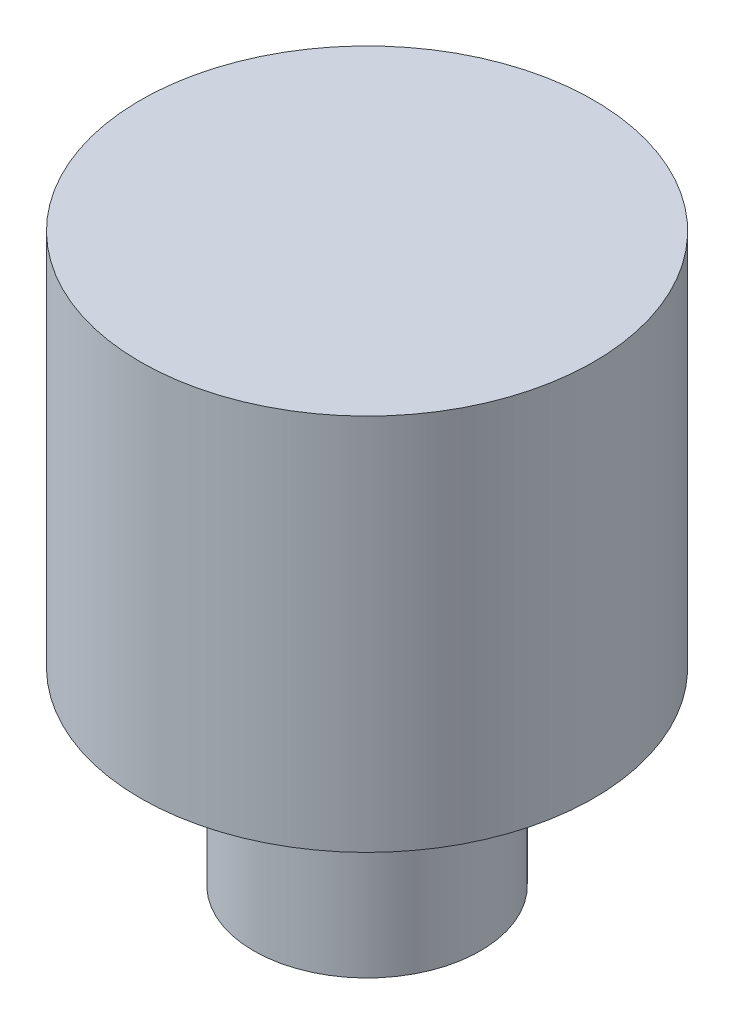
SolidWorks part; units mm, degrees
ref_plane "Front Plane" through (0, 0, 0) normal (0, 0, 1) x (1, 0, 0)
ref_plane "Top Plane" through (0, 0, 0) normal (0, 1, 0) x (1, 0, 0)
ref_plane "Right Plane" through (0, 0, 0) normal (1, 0, 0) x (0, 0, -1)
sketch "Sketch1" plane through (0, 0, 0) normal (0, 1, 0) x (1, 0, 0)
  circle A0 centre (0, 0) radius 76.2
extrude "Boss-Extrude1" add sketch "Sketch1" along normal blind 127
sketch "Sketch2" plane through (0, 0, 0) normal (0, -1, 0) x (1, 0, 0)
  circle A0 centre (0, 0) radius 38.1
extrude "Boss-Extrude2" add sketch "Sketch2" along normal blind 63.5
